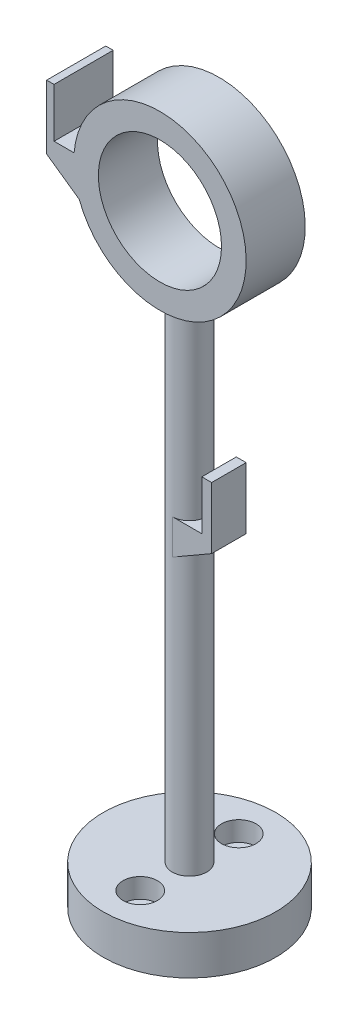
SolidWorks part; units mm, degrees
ref_plane "Plano frontal" through (0, 0, 0) normal (0, 0, 1) x (1, 0, 0)
ref_plane "Plano superior" through (0, 0, 0) normal (0, 1, 0) x (1, 0, 0)
ref_plane "Plano direito" through (0, 0, 0) normal (1, 0, 0) x (0, 0, -1)
sketch "Esboço1" plane through (0, 0, 0) normal (0, 1, 0) x (1, 0, 0)
  line L0 (0, 17.5) -> (0, -17.5) construction
  circle A0 centre (0, 0) radius 17.5
  circle A1 centre (0, 0) radius 5.0209
  dimension "D1" = 35
extrude "Ressalto-extrusão1" add sketch "Esboço1" along normal blind 8 contours A0
sketch "Esboço2" plane through (0, 8, 0) normal (0, 1, 0) x (1, 0, 0)
  circle A0 centre (0, 0) radius 3.5
  dimension "D1" = 7
extrude "Ressalto-extrusão2" add sketch "Esboço2" along normal blind 100
sketch "Esboço3" plane through (0, 8, 0) normal (0, 1, 0) x (1, 0, 0)
  line L0 (0, -17.5) -> (0, 17.5) construction
  circle A0 centre (0, 0) radius 17.5 construction
  circle A1 centre (0, 10) radius 3.5
  circle A2 centre (0, -10) radius 3.5
  dimension "D3" = 7
  dimension "D4" = 7
  dimension "D1" = 10
  dimension "D2" = 10
extrude "Corte-extrusão1" cut sketch "Esboço3" against normal blind 4
sketch "Esboço4" plane through (0, 4, 0) normal (0, 1, 0) x (1, 0, 0)
  circle A0 centre (0, 10) radius 2
  circle A1 centre (0, -10) radius 2
  circle A2 centre (0, 10) radius 3.5 construction
  point P5 (0, 0)
  dimension "D1" = 4
  dimension "D2" = 4
extrude "Corte-extrusão2" cut sketch "Esboço4" against normal blind 4
sketch "Esboço5" plane through (0, 0, 0) normal (0, 0, 1) x (1, 0, 0)
  line L0 (3.5, 108) -> (-3.5, 108) construction
  circle A0 centre (0, 125.5) radius 12.5
  circle A1 centre (0, 125.5) radius 17.5
  point P5 (0, 0)
  dimension "D1" = 25
  dimension "D2" = 35
extrude "Ressalto-extrusão3" add sketch "Esboço5" along normal mid plane 12 separate body
sketch "Esboço8" plane through (0, 0, 0) normal (1, 0, 0) x (0, 0, -1)
  line L0 (-3.5, 70.5) -> (3.5, 70.5)
  line L1 (3.5, 8) -> (3.5, 108) construction
  line L2 (3.5, 70.5) -> (3.5, 68)
  line L3 (3.5, 8) -> (3.5, 108) construction
  line L4 (3.5, 68) -> (-3.5, 68)
  line L5 (-3.5, 108) -> (-3.5, 8) construction
  line L6 (-3.5, 68) -> (-3.5, 70.5)
  line L7 (3.5, 8) -> (-3.5, 8) construction
  dimension "D1" = 60
  dimension "D2" = 2.5
  dimension "D3" = 180
extrude "Ressalto-extrusão4" add sketch "Esboço8" along normal blind 8
sketch "Esboço9" plane through (0, 70.5, 0) normal (0, 1, 0) x (1, 0, 0)
  line L0 (8, -3.5) -> (6, -3.5)
  line L1 (8, -3.5) -> (0, -3.5) construction
  line L2 (6, -3.5) -> (6, 3.5)
  line L3 (8, 3.5) -> (0, 3.5) construction
  line L4 (6, 3.5) -> (8, 3.5)
  line L5 (8, 3.5) -> (8, -3.5)
  dimension "D1" = 2
extrude "Ressalto-extrusão5" add sketch "Esboço9" along normal blind 10
ref_plane "Plano1" through (-15, 0, 0) normal (-1, 0, 0) x (0, 0, 1)
sketch "Esboço12" plane through (0, 0, 0) normal (0, 0, 1) x (1, 0, 0)
  point P0 (0, 125.5)
  point P1 (0, 0)
  point P3 (0, 0)
sketch "Esboço14" plane through (-15, 0, 0) normal (-1, 0, 0) x (0, 0, 1)
  line L0 (6, 125.5) -> (6, 127)
  line L2 (6, 108) -> (6, 143) construction
  line L3 (6, 125.5) -> (6, 124)
  line L4 (6, 124) -> (-6, 124)
  line L5 (-6, 138) -> (-6, 113) construction
  line L6 (-6, 124) -> (-6, 127)
  line L7 (-6, 127) -> (6, 127)
  dimension "D1" = 1.5
  dimension "D2" = 1.5
extrude "Ressalto-extrusão6" add sketch "Esboço14" along normal blind 8
sketch "Esboço15" plane through (0, 127, 0) normal (0, 1, 0) x (1, 0, 0)
  line L0 (-23, -6) -> (-17.4356, -6) construction
  line L1 (-23, 6) -> (-21.5, 6)
  line L2 (-23, 6) -> (-23, -6)
  line L3 (-23, -6) -> (-21.5, -6)
  line L4 (-21.5, 6) -> (-21.5, -6)
  dimension "D1" = 1.5
extrude "Ressalto-extrusão7" add sketch "Esboço15" along normal blind 10
sketch "Esboço16" plane through (0, 0, 0) normal (0, 0, 1) x (1, 0, 0)
  line L0 (-23, 124) -> (-16.3785, 119.3361)
  line L1 (-16.3785, 119.3361) -> (-17.4356, 124)
  line L2 (-17.4356, 124) -> (-23, 124)
  arc A0 (-17.4356, 124) -> (-17.4356, 127) centre (0, 125.5) ccw construction
  dimension "D1" = 8.0991
extrude "Ressalto-extrusão8" add sketch "Esboço16" along normal mid plane 12
sketch "Esboço17" plane through (0, 0, 0) normal (0, 0, 1) x (1, 0, 0)
  line L0 (8, 68) -> (0, 63.3812)
  line L1 (0, 63.3812) -> (0, 68)
  line L9 (0, 70.5) -> (0, 68)
  line L10 (0, 68) -> (8, 68)
  line L11 (8, 68) -> (8, 80.5)
  line L12 (8, 80.5) -> (6, 80.5)
  line L13 (6, 80.5) -> (6, 70.5)
  line L14 (6, 70.5) -> (0, 70.5)
  line L16 (0, 68) -> (8, 68)
  dimension "D1" = 9.2376
  dimension "D2" = 0
extrude "Ressalto-extrusão9" add sketch "Esboço17" along normal mid plane 7
